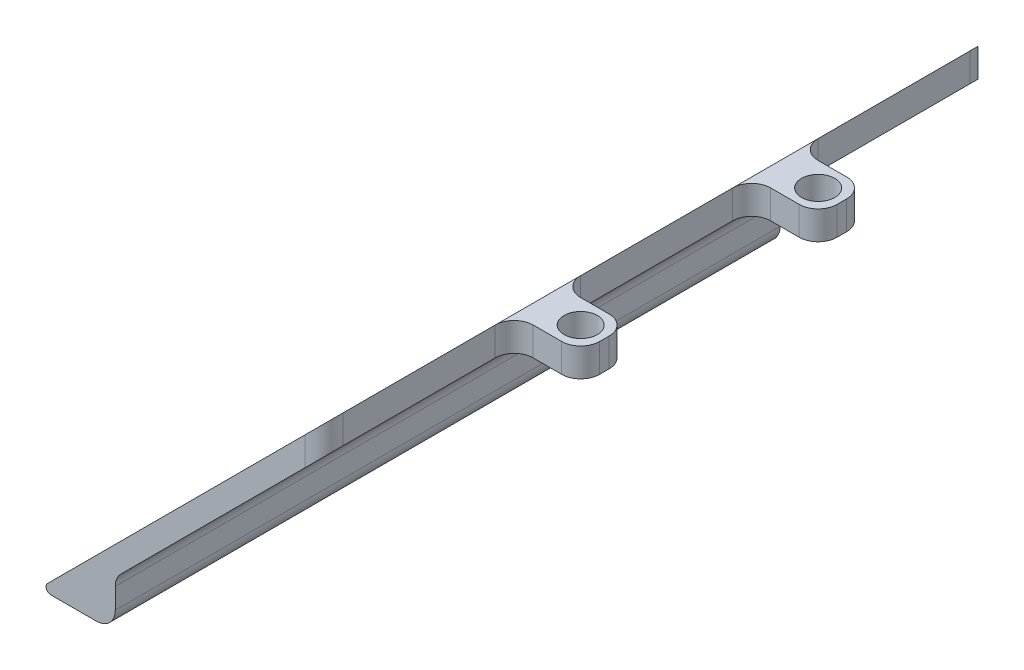
SolidWorks part; units mm, degrees
ref_plane "前视基准面" through (0, 0, 0) normal (0, 0, 1) x (1, 0, 0)
ref_plane "上视基准面" through (0, 0, 0) normal (0, 1, 0) x (1, 0, 0)
ref_plane "右视基准面" through (0, 0, 0) normal (1, 0, 0) x (0, 0, -1)
sketch "草图1" plane through (0, 0, 0) normal (0, 0, 1) x (1, 0, 0)
  line L0 (40.766, 35.4982) -> (40.766, 5.4982)
  line L1 (40.766, 5.4982) -> (10.766, 5.4982)
  line L2 (10.766, 5.4982) -> (40.766, 35.4982)
  line L3 (40.766, 32.4982) -> (13.766, 5.4982)
  line L4 (40.766, 32.4982) -> (47.766, 32.4982)
  line L5 (47.766, 32.4982) -> (47.766, 35.4982)
  line L6 (47.766, 35.4982) -> (40.766, 35.4982)
  line L7 (13.766, 5.4982) -> (18.766, 5.4982)
  line L8 (18.766, 5.4982) -> (18.766, 10.4982)
  dimension "D1" = 30
  dimension "D2" = 30
  dimension "D3" = 3
  dimension "D4" = 3
  dimension "D5" = 7
extrude "凸台-拉伸1" add sketch "草图1" along normal blind 70 contours L5 L6 L0 L4 | L3 L0 L2 L1 | L1 L8 L3
sketch "草图2" plane through (0, 35.4982, 0) normal (0, 1, 0) x (1, 0, 0)
  line L0 (47.766, -70) -> (47.766, 0) construction
  line L1 (47.766, 0) -> (40.766, 0) construction
  circle A0 centre (45.266, -22.5) radius 1.75
  circle A1 centre (45.266, -47.5) radius 1.75
  dimension "D1" = 3.5
  dimension "D2" = 3.5
  dimension "D3" = 25
  dimension "D4" = 2.5
  dimension "D5" = 2.5
  dimension "D6" = 22.5
extrude "切除-拉伸1" cut sketch "草图2" against normal blind 70
sketch "草图3" plane through (0, 35.4982, 0) normal (0, 1, 0) x (1, 0, 0)
  line L0 (47.766, -70) -> (47.766, 0) construction
  line L1 (40.766, 0) -> (47.766, 0)
  line L2 (40.766, 0) -> (40.766, -20)
  line L3 (40.766, -20) -> (47.766, -20)
  line L4 (47.766, 0) -> (47.766, -20)
  line L6 (40.766, -70) -> (47.766, -70)
  line L7 (40.766, -70) -> (40.766, -50)
  line L8 (40.766, -50) -> (47.766, -50)
  line L9 (47.766, -70) -> (47.766, -50)
extrude "切除-拉伸2" cut sketch "草图3" against normal blind 70
fillet "圆角1" radius 2 2 edges at (40.766, 33.9982, 20) (40.766, 33.9982, 50)
fillet "圆角3" radius 2 2 edges at (40.766, 33.9982, 70) (40.766, 33.9982, 0)
fillet "圆角4" radius 2 2 edges at (18.766, 5.4982, 35) (18.766, 10.4982, 35)
fillet "圆角5" radius 2 2 edges at (47.766, 33.9982, 20) (47.766, 33.9982, 50)
sketch "草图4" plane through (47.766, 0, 0) normal (1, 0, 0) x (0, 0, -1)
  line L0 (-48, 35.4982) -> (-22, 35.4982) construction
  line L1 (-45, 35.4982) -> (-25, 35.4982)
  line L2 (-45, 35.4982) -> (-45, 32.4982)
  line L3 (-45, 32.4982) -> (-25, 32.4982)
  line L4 (-25, 35.4982) -> (-25, 32.4982)
  line L5 (-48, 32.4982) -> (-22, 32.4982) construction
  line L7 (-20, 35.4982) -> (-20, 32.4982) construction
  dimension "D1" = 20
  dimension "D2" = 5
extrude "切除-拉伸3" cut sketch "草图4" against normal blind 7
fillet "圆角6" radius 2 4 edges at (47.766, 33.9982, 25) (40.766, 33.9982, 25) (40.766, 33.9982, 45) (47.766, 33.9982, 45)
fillet "圆角7" radius 0.5 1 edges at (10.766, 5.4982, 35)
sketch "草图5" plane through (2.6339, -2.6339, 0) normal (-0.7071, 0.7071, 0) x (0, 0, 1)
  line L0 (27, 53.927) -> (43, 53.927) construction
  line L1 (8.5, 43.927) -> (61.5, 43.927)
  line L2 (8.5, 43.927) -> (8.5, 25.427)
  line L3 (8.5, 25.427) -> (61.5, 25.427)
  line L4 (61.5, 43.927) -> (61.5, 25.427)
  point P4 (35, 43.927)
  point P7 (35, 53.927)
  dimension "D1" = 18.5
  dimension "D2" = 53
  dimension "D3" = 0
  dimension "D4" = 10
extrude "切除-拉伸4" cut sketch "草图5" against normal blind 8
sketch "草图7" plane through (2.6339, -2.6339, 0) normal (-0.7071, 0.7071, 0) x (0, 0, 1)
  line L1 (13.25, 39.177) -> (15.5, 39.177)
  line L3 (13.25, 30.177) -> (15.5, 30.177)
  line L4 (15.5, 39.177) -> (15.5, 30.177)
  line L5 (61.5, 25.427) -> (61.5, 43.927) construction
  line L6 (56.75, 30.177) -> (54.5, 30.177)
  line L8 (56.75, 39.177) -> (54.5, 39.177)
  line L9 (54.5, 30.177) -> (54.5, 39.177)
  line L10 (61.5, 43.927) -> (8.5, 43.927) construction
  line L11 (8.5, 25.427) -> (61.5, 25.427) construction
  line L15 (13.25, 43.927) -> (13.25, 39.177)
  line L16 (8.5, 25.427) -> (13.25, 25.427)
  line L19 (13.25, 25.427) -> (13.25, 30.177)
  line L22 (61.5, 43.927) -> (56.75, 43.927)
  line L23 (56.75, 39.177) -> (56.75, 43.927)
  line L25 (61.5, 35.177) -> (61.5, 25.427)
  line L26 (61.5, 25.427) -> (56.75, 25.427)
  line L27 (56.75, 30.177) -> (56.75, 25.427)
  line L28 (61.5, 43.927) -> (61.5, 35.177)
  line L29 (8.5, 43.927) -> (8.5, 25.427)
  line L30 (13.25, 43.927) -> (8.5, 43.927)
  circle A0 centre (12.5, 34.677) radius 1.75
  circle A1 centre (57.5, 34.677) radius 1.75
  point P8 (54.5, 34.677)
  point P32 (15.5, 34.677)
  dimension "D8" = 3.5
  dimension "D9" = 0
  dimension "D10" = 7
  dimension "D11" = 3.5
  dimension "D4" = 0
  dimension "D12" = 4
  dimension "D1" = 9
  dimension "D2" = 4.75
  dimension "D3" = 9
  dimension "D5" = 4.75
  dimension "D6" = 4.75
  dimension "D7" = 4.75
  dimension "D13" = 7
extrude "凸台-拉伸3" add sketch "草图7" against normal up to surface (2.1213 mm away) up to face at (28.6542, 20.3864, 35)
fillet "圆角9" radius 1 12 edges at (34.445, 27.6771, 13.25) (34.445, 27.6771, 56.75) (31.0862, 24.3184, 56.75) (31.0862, 24.3184, 54.5) (24.7223, 17.9544, 54.5) (24.7223, 17.9544, 56.75) (21.3635, 14.5957, 56.75) (21.3635, 14.5957, 13.25) (24.7223, 17.9544, 13.25) (24.7223, 17.9544, 15.5) (31.0862, 24.3184, 15.5) (31.0862, 24.3184, 13.25)
